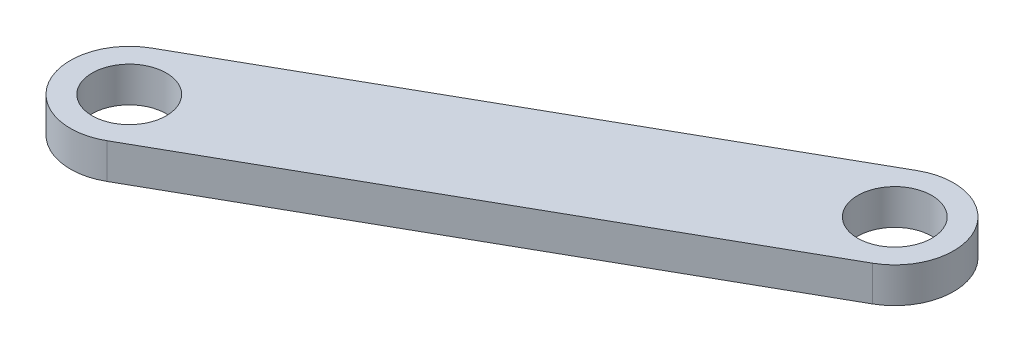
SolidWorks part; units mm, degrees
material "6061-T6 (SS)"
ref_plane "X-Y Datum" through (0, 0, 0) normal (0, 0, 1) x (1, 0, 0)
ref_plane "X-Z Datum" through (0, 0, 0) normal (0, 1, 0) x (1, 0, 0)
ref_plane "Y-Z Datum" through (0, 0, 0) normal (1, 0, 0) x (0, 0, -1)
sketch "Sketch1" plane through (0, 0, 0) normal (0, 1, 0) x (1, 0, 0)
  line L0 (1.564, -2.7631) -> (-24.7986, -17.6856)
  line L1 (-1.564, 2.7631) -> (-27.9266, -12.1594)
  line L2 (0, 0) -> (-26.3626, -14.9225) construction
  circle A0 centre (0, 0) radius 2
  circle A1 centre (-26.3626, -14.9225) radius 2
  arc A2 (-24.7986, -17.6856) -> (-27.9266, -12.1594) centre (-26.3626, -14.9225) cw
  arc A3 (-1.564, 2.7631) -> (1.564, -2.7631) centre (0, 0) cw
  dimension "D1" = 4
  dimension "D2" = 14.9225
  dimension "D5" = 3.175
  dimension "D3" = 26.3626
extrude "Boss-Extrude1" add sketch "Sketch1" against normal blind 1.905
